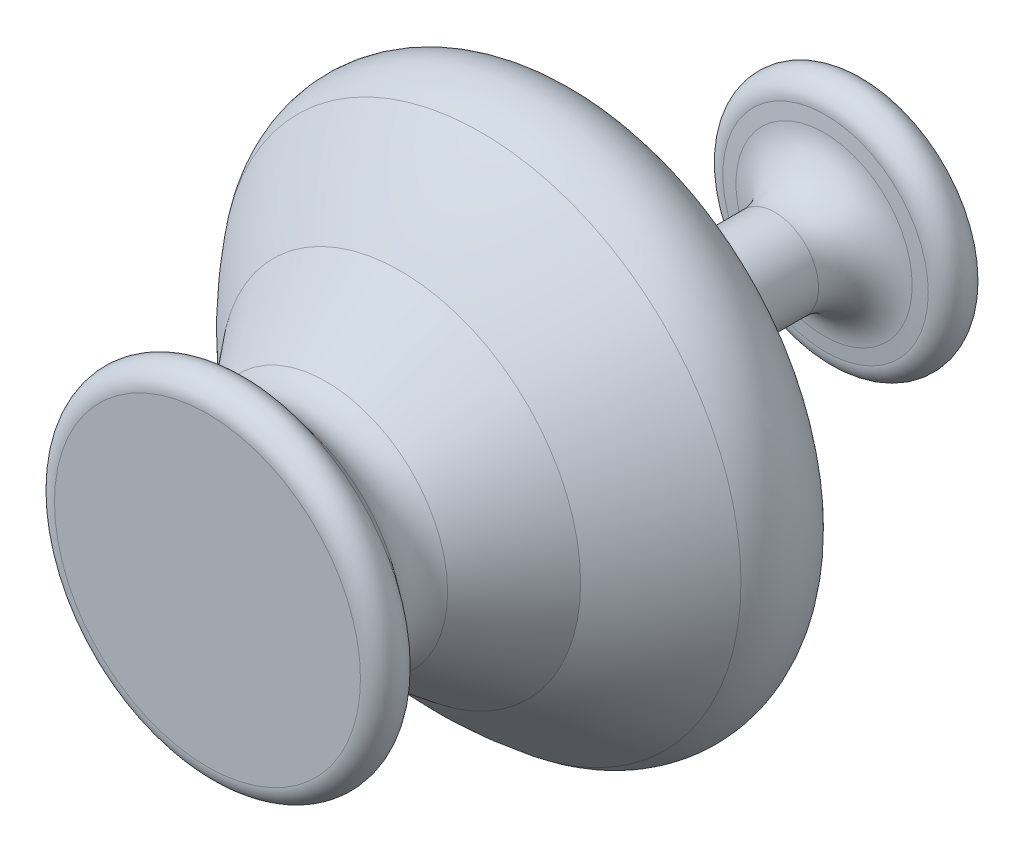
SolidWorks part; units mm, degrees
ref_plane "Front Plane" through (0, 0, 0) normal (0, 0, 1) x (1, 0, 0)
ref_plane "Top Plane" through (0, 0, 0) normal (0, 1, 0) x (1, 0, 0)
ref_plane "Right Plane" through (0, 0, 0) normal (1, 0, 0) x (0, 0, -1)
sketch "Sketch1" plane through (0, 0, 0) normal (0, 1, 0) x (1, 0, 0)
  line L0 (0, 0) -> (-37.1292, 0)
  line L1 (-40.2161, 8.9333) -> (-31.0289, 16.1436)
  line L2 (-29.5053, 28.78) -> (-43.6966, 46.8624)
  line L3 (-58.3094, 90.3239) -> (-16.7511, 113.5219)
  line L4 (0, 0) -> (0, 188.7247) construction
  line L5 (-10.6, 124) -> (-10.6, 137.7)
  line L6 (-21.38, 149.6378) -> (-24.9238, 150)
  line L10 (-24.9238, 160) -> (-14.4238, 160)
  line L11 (0, 4.4) -> (-37.1292, 4.4)
  line L12 (-37.4996, 5.472) -> (-28.3124, 12.6822)
  line L13 (-26.044, 31.4965) -> (-40.5454, 49.974)
  line L14 (-56.1648, 86.4819) -> (-14.6065, 109.68)
  line L15 (-6.2, 124) -> (-6.2, 137.7)
  line L16 (-20.9326, 154.015) -> (-24.8087, 154.4112)
  line L17 (-24.9238, 155.6) -> (-14.4238, 155.6)
  line L18 (-14.4238, 160) -> (-14.4238, 155.6)
  line L19 (0, 0) -> (0, 4.4)
  arc A0 (-40.2161, 8.9333) -> (-37.1292, 0) centre (-37.1292, 5) ccw
  arc A1 (-29.5053, 28.78) -> (-31.0289, 16.1436) centre (-36.5853, 23.2235) cw
  arc A2 (-43.6966, 46.8624) -> (-63.0541, 66.42) centre (34.7836, 143.898) cw
  arc A3 (-58.3094, 90.3239) -> (-63.0541, 66.42) centre (-50.5108, 76.3531) ccw
  arc A4 (-10.6, 124) -> (-16.7511, 113.5219) centre (-22.6, 124) cw
  arc A5 (-21.38, 149.6378) -> (-10.6, 137.7) centre (-22.6, 137.7) cw
  arc A6 (-24.9238, 150) -> (-24.9238, 160) centre (-24.9238, 155) cw
  arc A7 (-37.4996, 5.472) -> (-37.1292, 4.4) centre (-37.1292, 5) ccw
  arc A8 (-26.044, 31.4965) -> (-28.3124, 12.6822) centre (-36.5853, 23.2235) cw
  arc A9 (-40.5454, 49.974) -> (-59.6047, 69.1516) centre (34.7836, 143.898) cw
  arc A10 (-56.1648, 86.4819) -> (-59.6047, 69.1516) centre (-50.5108, 76.3531) ccw
  arc A11 (-6.2, 124) -> (-14.6065, 109.68) centre (-22.6, 124) cw
  arc A12 (-20.9326, 154.015) -> (-6.2, 137.7) centre (-22.6, 137.7) cw
  arc A13 (-24.8087, 154.4112) -> (-24.9238, 155.6) centre (-24.9238, 155) cw
  point P9 (-23.9489, 21.7)
  point P12 (-27.65, 22.1462)
  point P16 (-73.4967, 81.8462)
  point P25 (-29.9238, 155)
  point P50 (0, 0)
  dimension "D3" = 5
  dimension "D4" = 9
  dimension "D5" = 124.8
  dimension "D7" = 16
  dimension "D8" = 12
  dimension "D9" = 12
  dimension "D12" = 5
  dimension "D16" = 37.1292
  dimension "D1" = 27.65
  dimension "D2" = 21.7
  dimension "D6" = 59.7
  dimension "D10" = 13.7
  dimension "D11" = 10.6
  dimension "D13" = 15.5
  dimension "D14" = 160
  dimension "D17" = 63.0541
  dimension "D18" = 46.8624
  dimension "D19" = 19.1776
  dimension "D20" = 24.9238
  dimension "D21" = 14.4238
  dimension "D15" = 4.4
revolve "Revolve3" add sketch "Sketch1" angle 360 about L4
